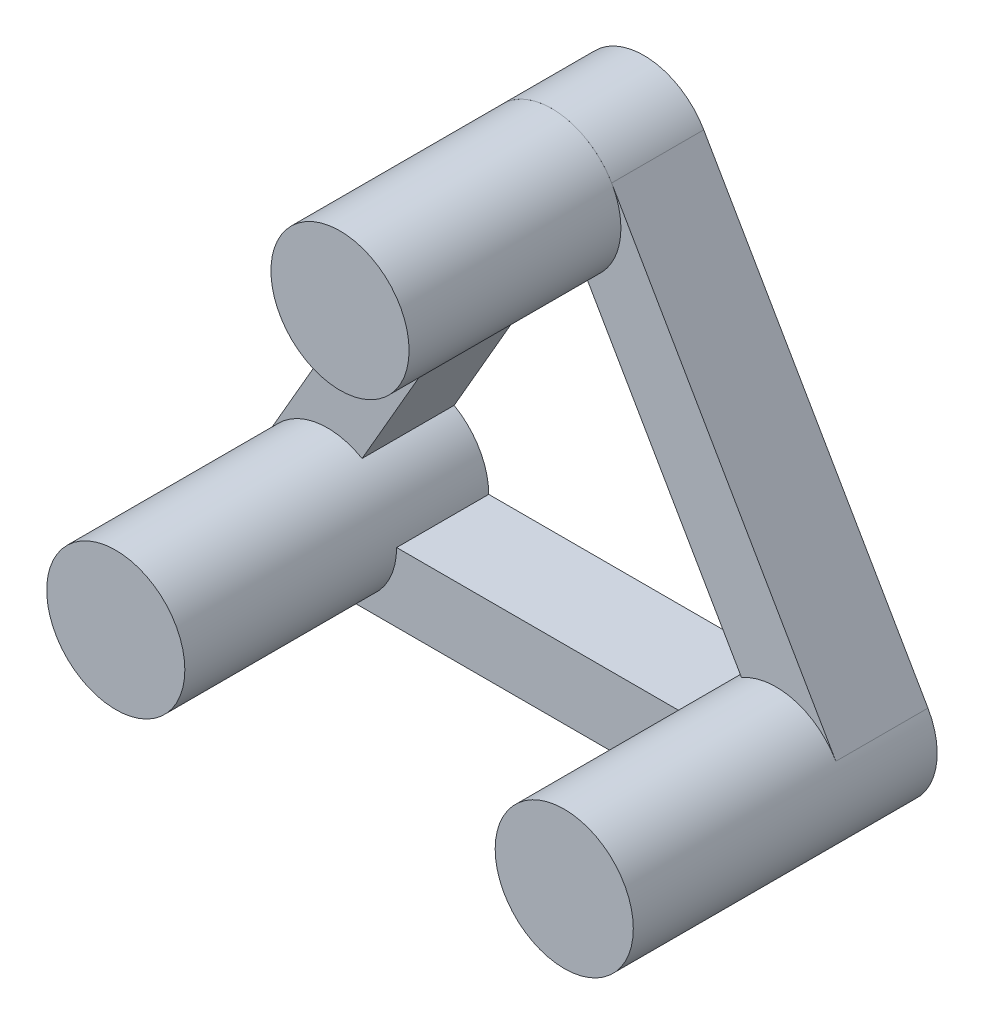
SolidWorks part; units mm, degrees
ref_plane "Alzado" through (0, 0, 0) normal (0, 0, 1) x (1, 0, 0)
ref_plane "Planta" through (0, 0, 0) normal (0, 1, 0) x (1, 0, 0)
ref_plane "Vista lateral" through (0, 0, 0) normal (1, 0, 0) x (0, 0, -1)
sketch "Croquis1" plane through (0, 0, 0) normal (0, 0, 1) x (1, 0, 0)
  line L2 (-0.6997, 4.3247) -> (-4.0704, -1.518)
  line L3 (-3.32, -2.8173) -> (3.42, -2.8173)
  line L4 (4.1704, -1.518) -> (0.7997, 4.3247)
  line L6 (-1.2496, 6.3739) -> (-6.1193, -2.0678)
  line L7 (-4.82, -4.3173) -> (4.92, -4.3173)
  line L8 (1.3496, 6.3739) -> (6.2193, -2.0678)
  arc A18 (-0.6997, 4.3247) -> (0.7997, 4.3247) centre (0.05, 5.6242) ccw
  arc A19 (4.92, -4.3173) -> (6.2193, -2.0678) centre (4.92, -2.8173) ccw
  arc A20 (-6.1193, -2.0678) -> (-4.82, -4.3173) centre (-4.82, -2.8173) ccw
  arc A21 (-3.32, -2.8173) -> (-4.0704, -1.518) centre (-4.82, -2.8173) ccw
  arc A22 (1.3496, 6.3739) -> (-1.2496, 6.3739) centre (0.05, 5.6242) ccw
  arc A23 (4.1704, -1.518) -> (3.42, -2.8173) centre (4.92, -2.8173) ccw
extrude "Saliente-Extruir1" add sketch "Croquis1" along normal blind 2
sketch "Croquis2" plane through (0, 0, 2) normal (0, 0, 1) x (1, 0, 0)
  circle A0 centre (0.05, 5.6242) radius 1.5
  circle A1 centre (4.92, -2.8173) radius 1.5
  circle A2 centre (-4.82, -2.8173) radius 1.5
  arc A3 (4.1704, -1.518) -> (3.42, -2.8173) centre (4.92, -2.8173) ccw construction
  arc A4 (-0.6997, 4.3247) -> (0.7997, 4.3247) centre (0.05, 5.6242) ccw construction
extrude "Saliente-Extruir4" add sketch "Croquis2" along normal blind 4.6
